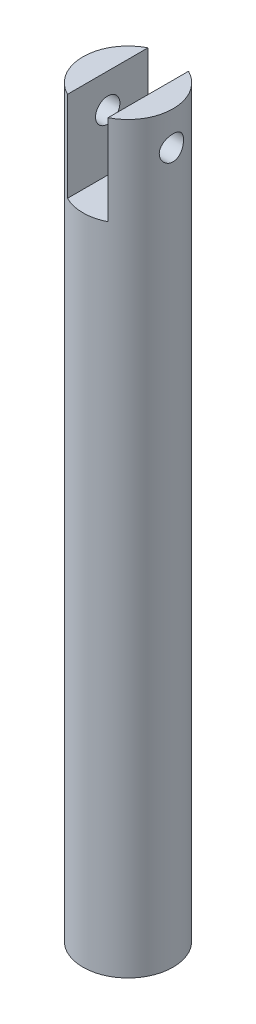
SolidWorks part; units mm, degrees
ref_plane "Front Plane" through (0, 0, 0) normal (0, 0, 1) x (1, 0, 0)
ref_plane "Top Plane" through (0, 0, 0) normal (0, 1, 0) x (1, 0, 0)
ref_plane "Right Plane" through (0, 0, 0) normal (1, 0, 0) x (0, 0, -1)
sketch "Sketch1" plane through (0, 0, 0) normal (0, 1, 0) x (1, 0, 0)
  circle A0 centre (0, 0) radius 10
  dimension "D1" = 20
extrude "Boss-Extrude1" add sketch "Sketch1" along normal blind 165
sketch "Sketch2" plane through (0, 0, 0) normal (0, 0, 1) x (1, 0, 0)
  line L0 (10, 165) -> (-10, 165) construction
  line L1 (-4.5, 185) -> (4.5, 185)
  line L2 (-4.5, 185) -> (-4.5, 145)
  line L3 (-4.5, 145) -> (4.5, 145)
  line L4 (4.5, 185) -> (4.5, 145)
  line L5 (0, 145) -> (0, 185) construction
  line L6 (-4.5, 165) -> (4.5, 165) construction
  point P0 (0, 165)
  dimension "D1" = 40
  dimension "D2" = 9
extrude "Cut-Extrude1" cut sketch "Sketch2" against normal through all both and the other way through all
sketch "Sketch3" plane through (0, 0, 0) normal (1, 0, 0) x (0, 0, -1)
  line L0 (8.9303, 165) -> (-8.9303, 165) construction
  circle A0 centre (0, 157.5) radius 2.7
  dimension "D1" = 5.4
  dimension "D2" = 7.5
extrude "Cut-Extrude2" cut sketch "Sketch3" against normal through all both and the other way through all
